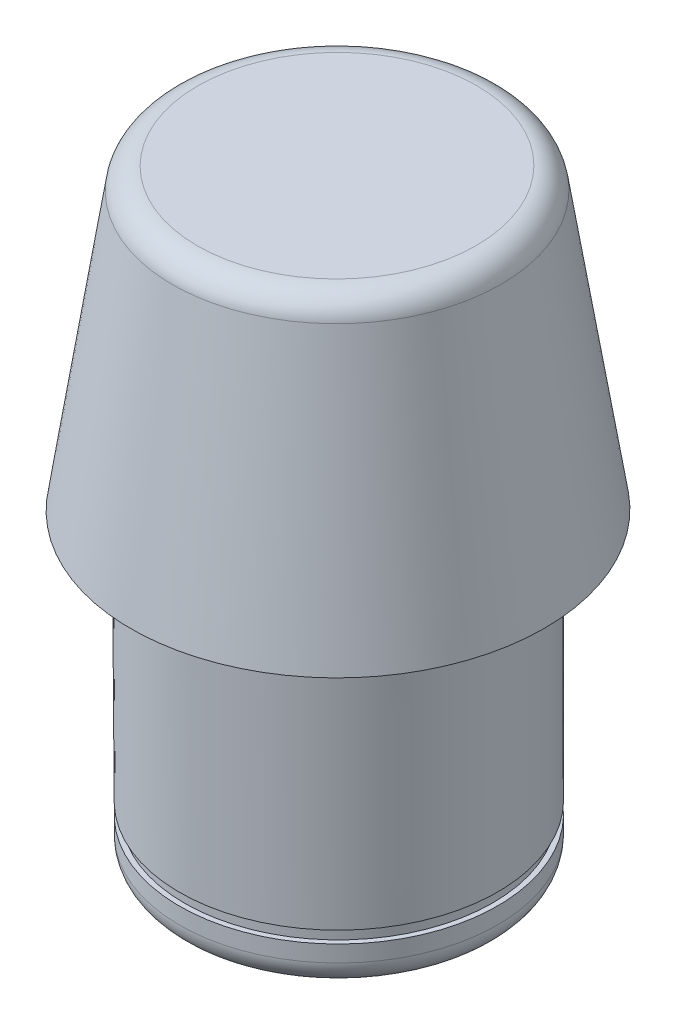
SolidWorks part; units mm, degrees
ref_plane "Front Plane" through (0, 0, 0) normal (0, 0, 1) x (1, 0, 0)
ref_plane "Top Plane" through (0, 0, 0) normal (0, 1, 0) x (1, 0, 0)
ref_plane "Right Plane" through (0, 0, 0) normal (1, 0, 0) x (0, 0, -1)
sketch "Sketch2" plane through (0, 0, 0) normal (0, 0, 1) x (1, 0, 0)
  line L0 (0, 0) -> (6.7564, 0)
  line L1 (8.0264, 2.1029) -> (8.0264, 1.27)
  line L3 (8.0264, 13.97) -> (10.3877, 15.4389)
  line L4 (10.3877, 15.4389) -> (8.1949, 29.407)
  line L5 (6.9402, 30.48) -> (-0.1016, 30.48)
  line L6 (8.0264, 2.1029) -> (7.7724, 2.1029)
  line L7 (7.7724, 2.1029) -> (7.7724, 2.7098)
  line L8 (7.7724, 2.7098) -> (8.0264, 2.7098)
  line L9 (-0.1016, 30.48) -> (0, 0) construction
  line L11 (-0.1016, 30.48) -> (0, 0)
  line L12 (8.0264, 2.7098) -> (8.0264, 13.97)
  arc A0 (8.0264, 1.27) -> (6.7564, 0) centre (6.7564, 1.27) cw
  arc A1 (6.9402, 30.48) -> (8.1949, 29.407) centre (6.9402, 29.21) cw
  dimension "D1" = 0.254
  dimension "D2" = 1.27
revolve "Revolve1" add sketch "Sketch2" angle 360 about L11
